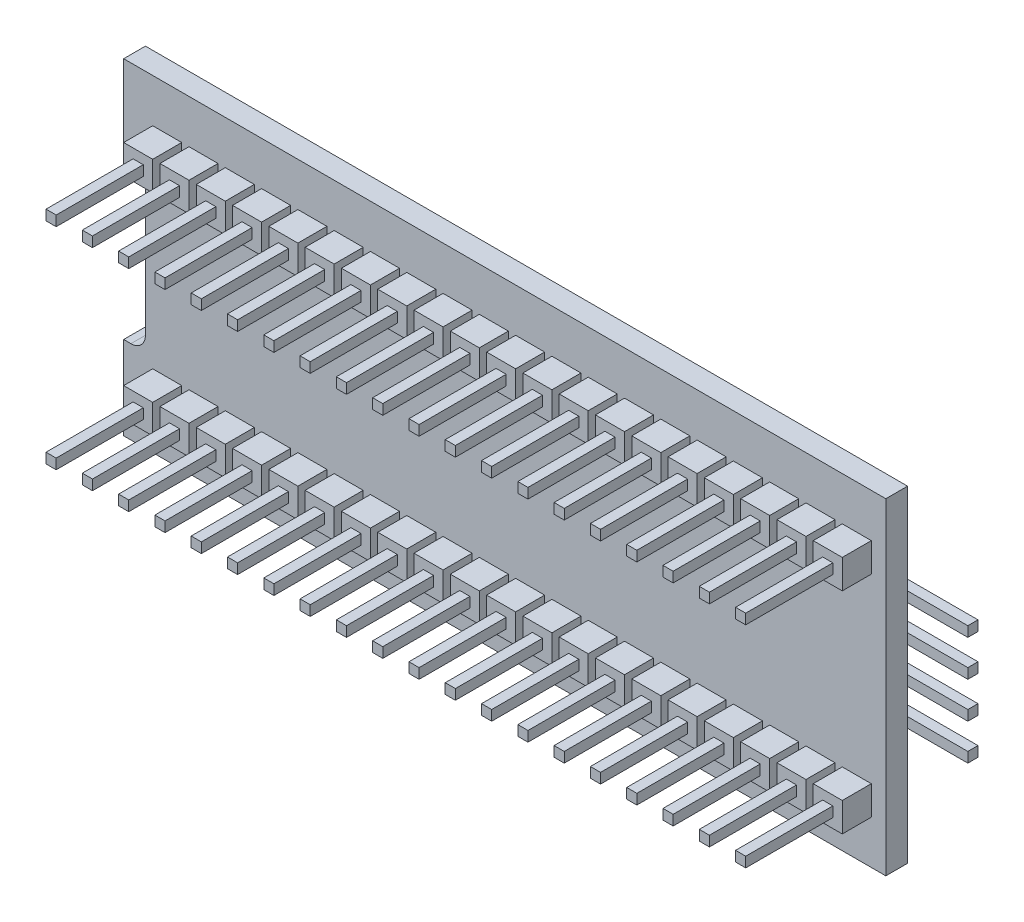
SolidWorks part; units mm, degrees
ref_plane "前视基准面" through (0, 0, 0) normal (0, 0, 1) x (1, 0, 0)
ref_plane "上视基准面" through (0, 0, 0) normal (0, 1, 0) x (1, 0, 0)
ref_plane "右视基准面" through (0, 0, 0) normal (1, 0, 0) x (0, 0, -1)
sketch "草图1" plane through (0, 0, 0) normal (0, 0, 1) x (1, 0, 0)
  line L1 (26.25, -11.25) -> (-26.25, -11.25)
  line L2 (26.25, -11.25) -> (26.25, 11.25)
  line L3 (26.25, 11.25) -> (-26.25, 11.25)
  line L4 (-26.25, -11.25) -> (-26.25, 11.25)
  line L5 (26.25, -11.25) -> (-26.25, 11.25) construction
  line L6 (26.25, 11.25) -> (-26.25, -11.25) construction
  point P0 (0, 0)
  dimension "D1" = 52.5
  dimension "D2" = 22.5
extrude "凸台-拉伸1" add sketch "草图1" along normal blind 1.5
sketch "草图2" plane through (0, 0, 0) normal (0, 0, -1) x (-1, 0, 0)
  line L0 (26.25, 5.5) -> (24.75, 5.5)
  line L1 (26.25, 11.25) -> (26.25, -11.25) construction
  line L2 (24.75, 5.5) -> (24.75, -5.5)
  line L3 (24.75, -5.5) -> (26.25, -5.5)
  line L4 (26.25, -5.5) -> (26.25, 5.5)
  line L5 (-26.25, 11.25) -> (26.25, 11.25) construction
  dimension "D1" = 11
  dimension "D2" = 5.75
  dimension "D3" = 1.5
extrude "切除-拉伸1" cut sketch "草图2" against normal up to next
fillet "圆角2" radius 1 1 edges at (-24.75, -5.5, 0.75)
fillet "圆角3" radius 1 1 edges at (-24.75, 5.5, 0.75)
sketch "草图3" plane through (0, 0, 0) normal (0, 0, -1) x (-1, 0, 0)
  line L0 (26.25, -5.5) -> (26.25, -11.25) construction
  line L1 (10.25, -0.25) -> (17.75, -0.25)
  line L2 (10.25, -0.25) -> (10.25, -5.25)
  line L3 (10.25, -5.25) -> (17.75, -5.25)
  line L4 (17.75, -0.25) -> (17.75, -5.25)
  line L5 (10.25, -0.25) -> (17.75, -5.25) construction
  line L6 (10.25, -5.25) -> (17.75, -0.25) construction
  line L7 (26.25, -11.25) -> (-26.25, -11.25) construction
  point P0 (14, -2.75)
  point P5 (10.25, -2.75)
  dimension "D1" = 16
  dimension "D2" = 6
  dimension "D3" = 7.5
  dimension "D4" = 5
extrude "凸台-拉伸2" add sketch "草图3" along normal blind 8.5
sketch "草图4" plane through (0, 0, 0) normal (0, 0, -1) x (-1, 0, 0)
  line L0 (-26.25, -11.25) -> (-26.25, 11.25) construction
  line L1 (-23.25, 2.5) -> (-21.25, 2.5)
  line L2 (-23.25, 2.5) -> (-23.25, 0.5)
  line L3 (-23.25, 0.5) -> (-21.25, 0.5)
  line L4 (-21.25, 2.5) -> (-21.25, 0.5)
  line L5 (-23.25, 2.5) -> (-21.25, 0.5) construction
  line L6 (-23.25, 0.5) -> (-21.25, 2.5) construction
  line L7 (-22.25, 12.2785) -> (-22.25, -14.3713) construction
  line L8 (-32.0494, 0) -> (32.3303, 0) construction
  point P0 (-22.25, 1.5)
  dimension "D1" = 2
  dimension "D2" = 2
  dimension "D3" = 3
  dimension "D4" = 0.5
extrude "凸台-拉伸3" add sketch "草图4" along normal blind 2
sketch "草图5" plane through (21.25, 0, 0) normal (-1, 0, 0) x (0, 0, 1)
  line L1 (-1.35, 1.15) -> (-0.65, 1.15)
  line L2 (-1.35, 1.15) -> (-1.35, 1.85)
  line L3 (-1.35, 1.85) -> (-0.65, 1.85)
  line L4 (-0.65, 1.15) -> (-0.65, 1.85)
  line L5 (-1.35, 1.15) -> (-0.65, 1.85) construction
  line L6 (-1.35, 1.85) -> (-0.65, 1.15) construction
  line L7 (-1, 0.4417) -> (-1, 2.7254) construction
  line L8 (-2, 0.5) -> (0, 0.5) construction
  line L9 (-2.1226, 1.5) -> (0.3709, 1.5) construction
  line L10 (-2, 0.5) -> (-2, 2.5) construction
  point P0 (-1, 1.5)
  point P9 (-1, 0.5)
  point P14 (-2, 1.5)
  point P15 (0, 0)
  dimension "D1" = 0.7
  dimension "D2" = 0.7
extrude "凸台-拉伸4" add sketch "草图5" against normal blind 8.5
pattern_linear "阵列(线性)1" count 2 spacing 2.5 along (0, 1, 0) count 3 spacing 2.5 along (0, -1, 0) of "凸台-拉伸4", "凸台-拉伸3"
sketch "草图7" plane through (0, 0, 1.5) normal (0, 0, 1) x (1, 0, 0)
  line L0 (-26.25, -11.25) -> (26.25, -11.25) construction
  line L1 (-24.25, -6.25) -> (-22.25, -6.25)
  line L2 (-24.25, -6.25) -> (-24.25, -8.25)
  line L3 (-24.25, -8.25) -> (-22.25, -8.25)
  line L4 (-22.25, -6.25) -> (-22.25, -8.25)
  line L5 (-24.25, -6.25) -> (-22.25, -8.25) construction
  line L6 (-24.25, -8.25) -> (-22.25, -6.25) construction
  line L7 (-26.25, -5.5) -> (-26.25, -11.25) construction
  point P0 (-23.25, -7.25)
  dimension "D1" = 2
  dimension "D2" = 2
  dimension "D3" = 3
  dimension "D4" = 2
extrude "凸台-拉伸5" add sketch "草图7" along normal blind 2
sketch "草图8" plane through (0, 0, 3.5) normal (0, 0, 1) x (1, 0, 0)
  line L0 (-24.25, -6.25) -> (-24.25, -8.25) construction
  line L1 (-23.6, -6.9) -> (-22.9, -6.9)
  line L2 (-23.6, -6.9) -> (-23.6, -7.6)
  line L3 (-23.6, -7.6) -> (-22.9, -7.6)
  line L4 (-22.9, -6.9) -> (-22.9, -7.6)
  line L5 (-23.6, -6.9) -> (-22.9, -7.6) construction
  line L6 (-23.6, -7.6) -> (-22.9, -6.9) construction
  line L7 (-22.25, -6.25) -> (-24.25, -6.25) construction
  point P0 (-23.25, -7.25)
  point P5 (0, 0)
  point P8 (-24.25, -7.25)
  point P11 (-23.25, -6.25)
  dimension "D1" = 0.7
  dimension "D2" = 0.7
extrude "凸台-拉伸6" add sketch "草图8" along normal blind 6
pattern_linear "阵列(线性)2" count 20 spacing 2.5 along (1, 0, 0) of "凸台-拉伸6", "凸台-拉伸5"
mirror "镜向1" about plane through (0, 0, 0) normal (0, 1, 0) of "阵列(线性)2", "凸台-拉伸5", "凸台-拉伸6"
